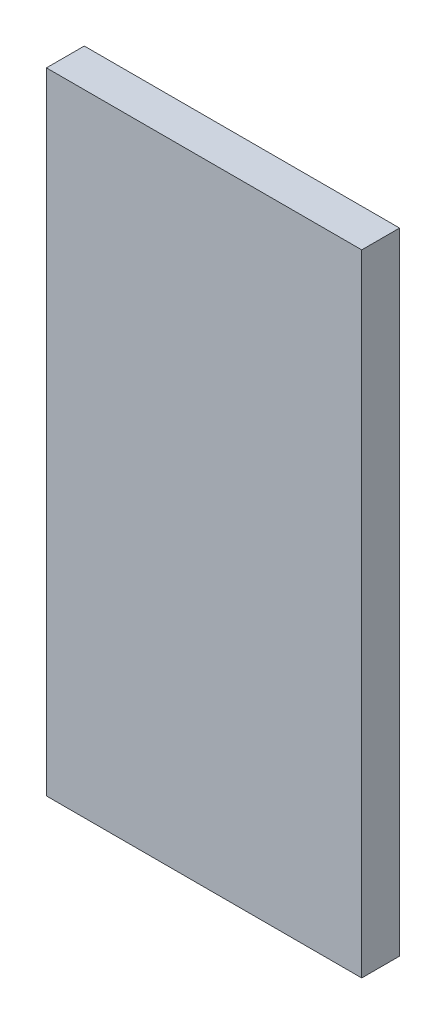
SolidWorks part; units mm, degrees
ref_plane "Plano frontal" through (0, 0, 0) normal (0, 0, 1) x (1, 0, 0)
ref_plane "Plano superior" through (0, 0, 0) normal (0, 1, 0) x (1, 0, 0)
ref_plane "Plano direito" through (0, 0, 0) normal (1, 0, 0) x (0, 0, -1)
sketch "Esboço1" plane through (0, 0, 0) normal (0, 0, 1) x (1, 0, 0)
  line L1 (101.3605, 19.7309) -> (86.3605, 19.7309)
  line L2 (101.3605, 19.7309) -> (101.3605, 49.7309)
  line L3 (101.3605, 49.7309) -> (86.3605, 49.7309)
  line L4 (86.3605, 19.7309) -> (86.3605, 49.7309)
extrude "Ressalto-extrusão1" add sketch "Esboço1" along normal blind 1.8
